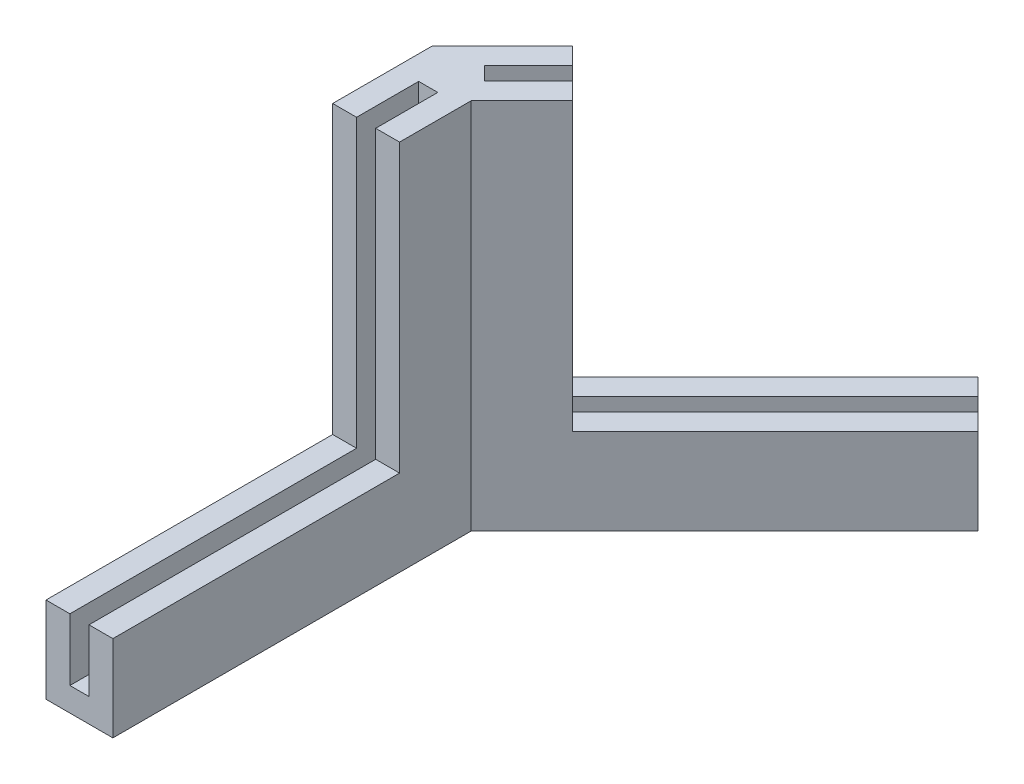
SolidWorks part; units mm, degrees
ref_plane "Front Plane" through (0, 0, 0) normal (0, 0, 1) x (1, 0, 0)
ref_plane "Top Plane" through (0, 0, 0) normal (0, 1, 0) x (1, 0, 0)
ref_plane "Right Plane" through (0, 0, 0) normal (1, 0, 0) x (0, 0, -1)
sketch "Sketch2" plane through (0, 0, 0) normal (0, 1, 0) x (1, 0, 0)
  line L0 (0, 0) -> (0, -15)
  line L1 (0, -15) -> (-5, -15)
  line L2 (-5, -15) -> (-5, -2)
  line L3 (-5, -2) -> (-9, -2)
  line L4 (-9, -2) -> (-9, -15)
  line L5 (-9, -15) -> (-14, -15)
  line L6 (0, 0) -> (-14, 5.799)
  line L7 (-14, -15) -> (-14, 5.799)
  point P8 (-0.3121, 0.1293)
  point P10 (0, 0)
  point P11 (0, 0)
  point P12 (0, 0)
  point P13 (0, 0)
  point P14 (0, 0)
  point P15 (0, 0)
  point P16 (0, 0)
  point P17 (0, 0)
  point P18 (-14, 5.799)
  point P19 (-14.1848, 5.799)
  point P20 (0, 0)
  point P21 (0, 0)
extrude "Boss-Extrude1" add sketch "Sketch2" along normal blind 78
mirror "Mirror1" about plane through (0, 78, 0) normal (-0.3827, 0, 0.9239) of "Boss-Extrude1"
sketch "Sketch4" plane through (1.4142, 0, -1.4142) normal (0.7071, 0, -0.7071) x (-0.7071, 0, -0.7071)
  line L0 (5, 78) -> (5, 0) construction
  line L1 (9, 0) -> (5, 0)
  line L2 (9, 0) -> (9, 5)
  line L3 (9, 5) -> (5, 5)
  line L4 (5, 0) -> (5, 5)
  dimension "D1" = 5
extrude "Boss-Extrude2" add sketch "Sketch4" along normal blind 13
sketch "Sketch5" plane through (0, 0, 2) normal (0, 0, 1) x (1, 0, 0)
  line L0 (-9, 78) -> (-9, 0) construction
  line L1 (-5, 0) -> (-9, 0)
  line L2 (-5, 0) -> (-5, 5)
  line L3 (-5, 5) -> (-9, 5)
  line L4 (-9, 0) -> (-9, 5)
  dimension "D1" = 5
extrude "Boss-Extrude3" add sketch "Sketch5" along normal blind 13
sketch "Sketch14" plane through (0, 0, 15) normal (0, 0, 1) x (1, 0, 0)
  line L0 (-14, 0) -> (0, 0)
  line L1 (-14, 0) -> (0, 0) construction
  line L2 (0, 78) -> (0, 0) construction
  line L3 (-14, 0) -> (-14, 18)
  line L4 (-14, 78) -> (-14, 0) construction
  line L5 (0, 0) -> (0, 18)
  line L6 (-14, 18) -> (-9, 18)
  line L7 (-9, 78) -> (-9, 5) construction
  line L8 (0, 18) -> (-5, 18)
  line L9 (-5, 18) -> (-5, 5)
  line L10 (-5, 5) -> (-9, 5)
  line L11 (-9, 5) -> (-9, 18)
  point P19 (0, 0)
extrude "Boss-Extrude6" add sketch "Sketch14" along normal blind 60
ref_plane "Plane1" through (0, 0, 0) normal (-0.3827, 0, 0.9239) x (0.9239, 0, 0.3827)
mirror "Mirror2" about plane through (0, 0, 0) normal (-0.3827, 0, 0.9239) of "Boss-Extrude6", "Boss-Extrude1"
